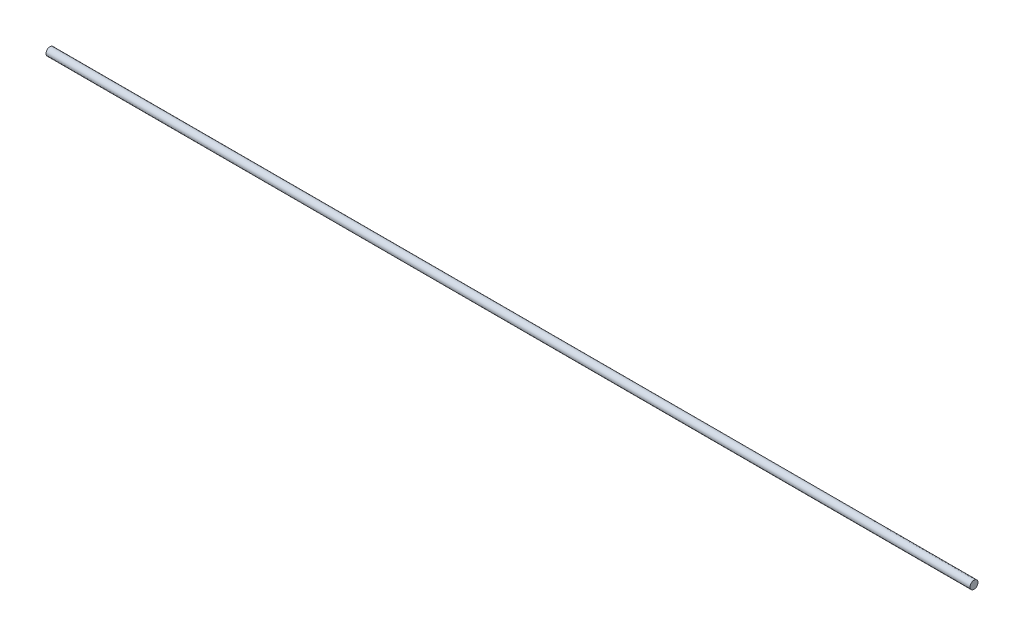
SolidWorks part; units mm, degrees
ref_plane "Front Plane" through (0, 0, 0) normal (0, 0, 1) x (1, 0, 0)
ref_plane "Top Plane" through (0, 0, 0) normal (0, 1, 0) x (1, 0, 0)
ref_plane "Right Plane" through (0, 0, 0) normal (1, 0, 0) x (0, 0, -1)
sketch "Sketch1" plane through (0, 0, 0) normal (1, 0, 0) x (0, 0, -1)
  circle A0 centre (0, 0) radius 3.5
  dimension "D1" = 7
extrude "Boss-Extrude1" add sketch "Sketch1" along normal blind 812.8
